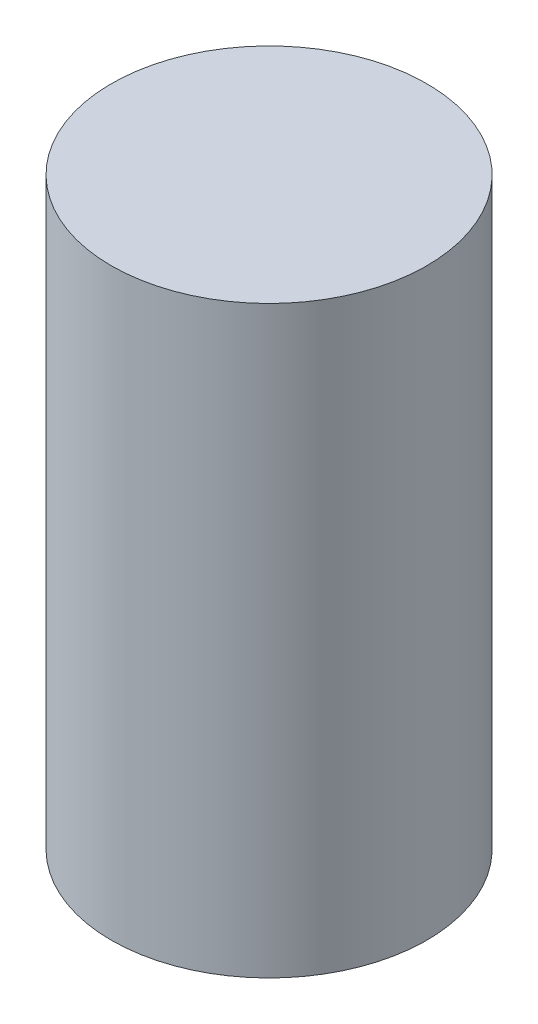
SolidWorks part; units mm, degrees
ref_plane "Front Plane" through (0, 0, 0) normal (0, 0, 1) x (1, 0, 0)
ref_plane "Top Plane" through (0, 0, 0) normal (0, 1, 0) x (1, 0, 0)
ref_plane "Right Plane" through (0, 0, 0) normal (1, 0, 0) x (0, 0, -1)
sketch "Sketch1" plane through (0, 0, 0) normal (0, 1, 0) x (1, 0, 0)
  circle A0 centre (0, 0) radius 13.5
  dimension "D1" = 27
extrude "Boss-Extrude1" add sketch "Sketch1" along normal blind 50
